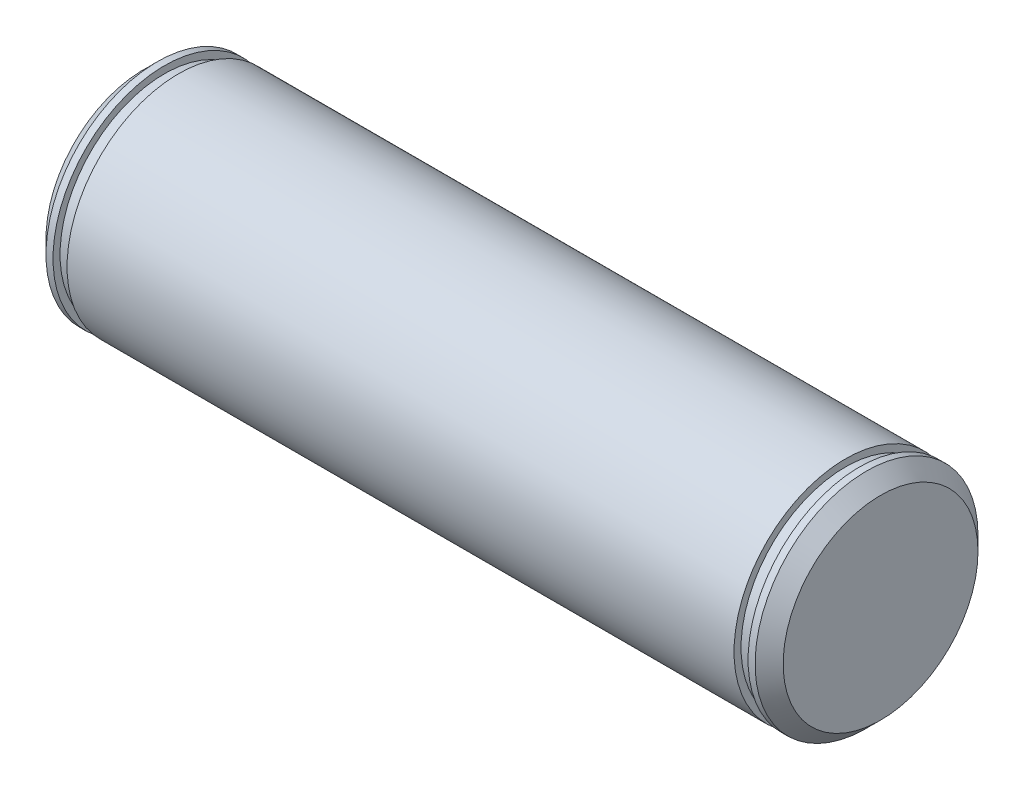
SolidWorks part; units mm, degrees
ref_plane "Front Plane" through (0, 0, 0) normal (0, 0, 1) x (1, 0, 0)
ref_plane "Top Plane" through (0, 0, 0) normal (0, 1, 0) x (1, 0, 0)
ref_plane "Right Plane" through (0, 0, 0) normal (1, 0, 0) x (0, 0, -1)
sketch "Sketch1" plane through (0, 0, 0) normal (1, 0, 0) x (0, 0, -1)
  circle A0 centre (0, 0) radius 15.875
  dimension "D1" = 31.75
extrude "Boss-Extrude1" add sketch "Sketch1" along normal mid plane 105
chamfer "Chamfer1" distance 2 angle 45 2 edges at (-52.5, 0, -15.875) (52.5, 0, -15.875)
ref_plane "Plane1" through (-47.5, 0, 0) normal (1, 0, 0) x (0, 0, -1)
sketch "Sketch2" plane through (-47.5, 0, 0) normal (1, 0, 0) x (0, 0, -1)
  circle A0 centre (0, 0) radius 15.875
  circle A1 centre (0, 0) radius 14.875
  dimension "D1" = 29.75
  dimension "D2" = 31.75
extrude "Cut-Extrude1" cut sketch "Sketch2" against normal blind 2
mirror "Mirror1" about plane through (0, 0, 0) normal (1, 0, 0) of "Cut-Extrude1"
